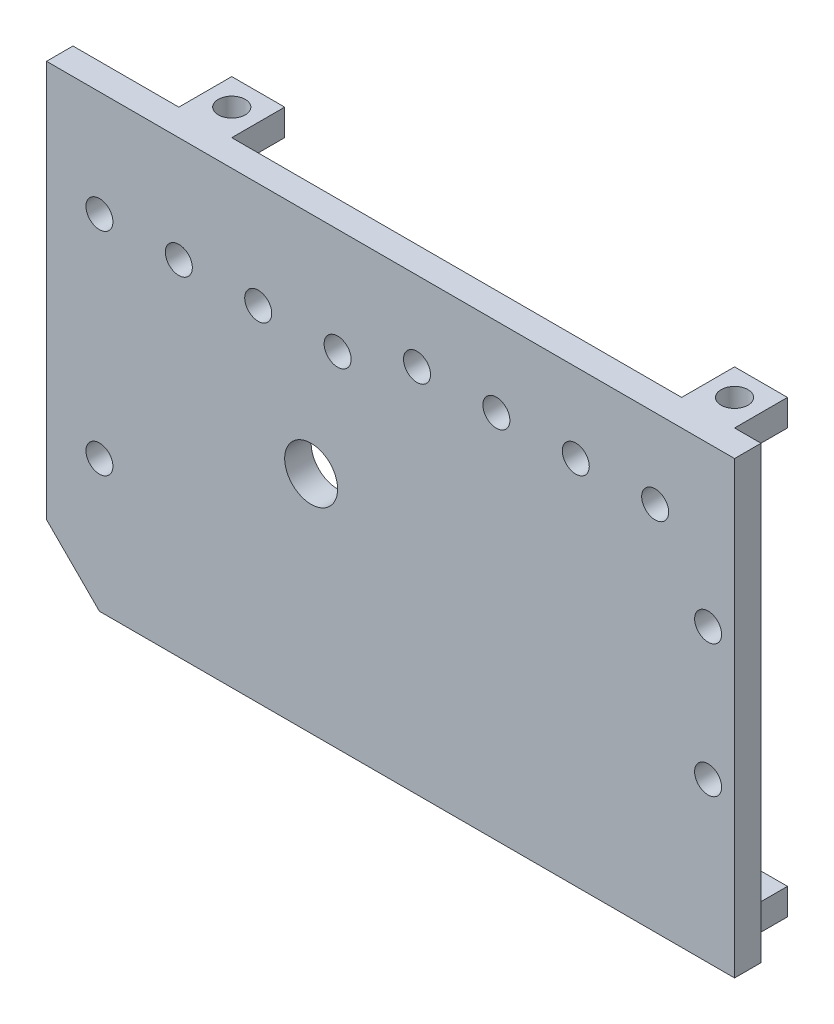
SolidWorks part; units mm, degrees
material "PLA+ esun"
ref_plane "Front Plane" through (0, 0, 0) normal (0, 0, 1) x (1, 0, 0)
ref_plane "Top Plane" through (0, 0, 0) normal (0, 1, 0) x (1, 0, 0)
ref_plane "Right Plane" through (0, 0, 0) normal (1, 0, 0) x (0, 0, -1)
sketch "Sketch1" plane through (0, 0, 0) normal (0, 0, 1) x (1, 0, 0)
  line L1 (-80, 42.5) -> (80, 42.5)
  line L2 (-80, 42.5) -> (-80, -42.5)
  line L3 (-80, -42.5) -> (80, -42.5)
  line L4 (80, 42.5) -> (80, -42.5)
  line L5 (-80, 42.5) -> (80, -42.5) construction
  line L6 (-80, -42.5) -> (80, 42.5) construction
  circle A0 centre (0, 0) radius 5
  point P0 (0, 0)
  dimension "D3" = 10
  dimension "D1" = 85
  dimension "D2" = 160
extrude "Boss-Extrude1" add sketch "Sketch1" along normal blind 5
sketch "Sketch3" plane through (0, 0, 5) normal (0, 0, 1) x (1, 0, 0)
  line L0 (-80, -42.5) -> (80, -42.5) construction
  line L1 (-80, 42.5) -> (-50, 42.5)
  line L2 (-80, 42.5) -> (-80, -42.5)
  line L3 (-80, -42.5) -> (-50, -42.5)
  line L4 (-50, 42.5) -> (-50, -42.5)
  dimension "D1" = 30
extrude "Cut-Extrude2" cut sketch "Sketch3" against normal blind 15
sketch "Sketch5" plane through (0, 0, 5) normal (0, 0, 1) x (1, 0, 0)
  line L0 (80, 42.5) -> (-50, 42.5) construction
  line L2 (80, -42.5) -> (80, 42.5) construction
  circle A0 centre (65, 27.5) radius 2.55
  circle A1 centre (50, 27.5) radius 2.55
  circle A2 centre (35, 27.5) radius 2.55
  circle A3 centre (20, 27.5) radius 2.55
  circle A8 centre (-40, 27.5) radius 2.55 [skipped]
  circle A9 centre (-25, 27.5) radius 2.55 [skipped]
  circle A10 centre (-10, 27.5) radius 2.55 [skipped]
  circle A11 centre (5, 27.5) radius 2.55 [skipped]
  circle A12 centre (5, 22.5) radius 2.55
  circle A13 centre (-10, 22.5) radius 2.55
  circle A14 centre (-25, 22.5) radius 2.55
  circle A15 centre (-40, 22.5) radius 2.55
  circle A17 centre (-40, -17.5) radius 2.55
  dimension "D1" = 5.1
  dimension "D2" = 15
  dimension "D3" = 15
  dimension "D5" = 15
  dimension "D6" = 5.1
  dimension "D7" = 15
  dimension "D8" = 20
  dimension "D10" = 2
  dimension "D4" = 8
  dimension "D9" = 4
extrude "Cut-Extrude3" cut sketch "Sketch5" against normal blind 15
chamfer "Chamfer1" distance 10 angle 45 1 edges at (-50, -42.5, 2.5)
sketch "Sketch6" plane through (0, 0, 0) normal (0, 0, -1) x (-1, 0, 0)
  line L0 (40, -42.5) -> (-80, -42.5) construction
  line L1 (-80, -42.5) -> (-75, -42.5)
  line L2 (-80, -42.5) -> (-80, -37.5)
  line L3 (-80, -37.5) -> (-75, -37.5)
  line L4 (-75, -42.5) -> (-75, -37.5)
  line L5 (-75, -37.5) -> (-65, -37.5)
  line L6 (-75, -37.5) -> (-75, -42.5)
  line L7 (-75, -42.5) -> (-65, -42.5)
  line L8 (-65, -37.5) -> (-65, -42.5)
  line L15 (50, -32.5) -> (50, 42.5) construction
  line L16 (30, -42.5) -> (20, -42.5)
  line L17 (30, -42.5) -> (30, -37.5)
  line L18 (30, -37.5) -> (20, -37.5)
  line L19 (20, -42.5) -> (20, -37.5)
  line M14 (-80, -42.5) -> (40, -42.5)
  dimension "D1" = 5
  dimension "D2" = 5
  dimension "D3" = 10
  dimension "D4" = 5
  dimension "D5" = 10
  dimension "D6" = 20
extrude "Boss-Extrude2" add sketch "Sketch6" along normal blind 10 contours L8 L5 L4 M14 | L19 L17 L18 M14
sketch "Sketch7" plane through (0, -37.5, 0) normal (0, 1, 0) x (1, 0, 0)
  line L0 (75, 10) -> (65, 10) construction
  line L1 (65, 10) -> (65, 0) construction
  line L2 (-30, 10) -> (-20, 10) construction
  line L3 (-20, 10) -> (-20, 0) construction
  circle A0 centre (70, 5) radius 2.55
  circle A1 centre (-25, 5) radius 2.55
  dimension "D1" = 5
  dimension "D2" = 5
  dimension "D3" = 5
  dimension "D4" = 5.1
  dimension "D5" = 5
  dimension "D6" = 5.1
extrude "Cut-Extrude4" cut sketch "Sketch7" against normal through all
ref_plane "Plane1" through (0, 0, 0) normal (0, 1, 0) x (1, 0, 0)
mirror "Mirror1" about plane through (0, 0, 0) normal (0, 1, 0) of "Boss-Extrude2"
mirror "Mirror2" about plane through (0, 0, 0) normal (0, 1, 0) of "Cut-Extrude4"
sketch "Sketch8" plane through (0, 0, 5) normal (0, 0, 1) x (1, 0, 0)
  line L0 (80, 42.5) -> (-50, 42.5) construction
  line L1 (80, -42.5) -> (80, 42.5) construction
  circle A0 centre (75, 12.5) radius 2.55
  circle A2 centre (75, -12.5) radius 2.55
  dimension "D1" = 5.1
  dimension "D2" = 30
  dimension "D3" = 5
  dimension "D5" = 25
  dimension "D4" = 2
extrude "Cut-Extrude5" cut sketch "Sketch8" against normal through all
